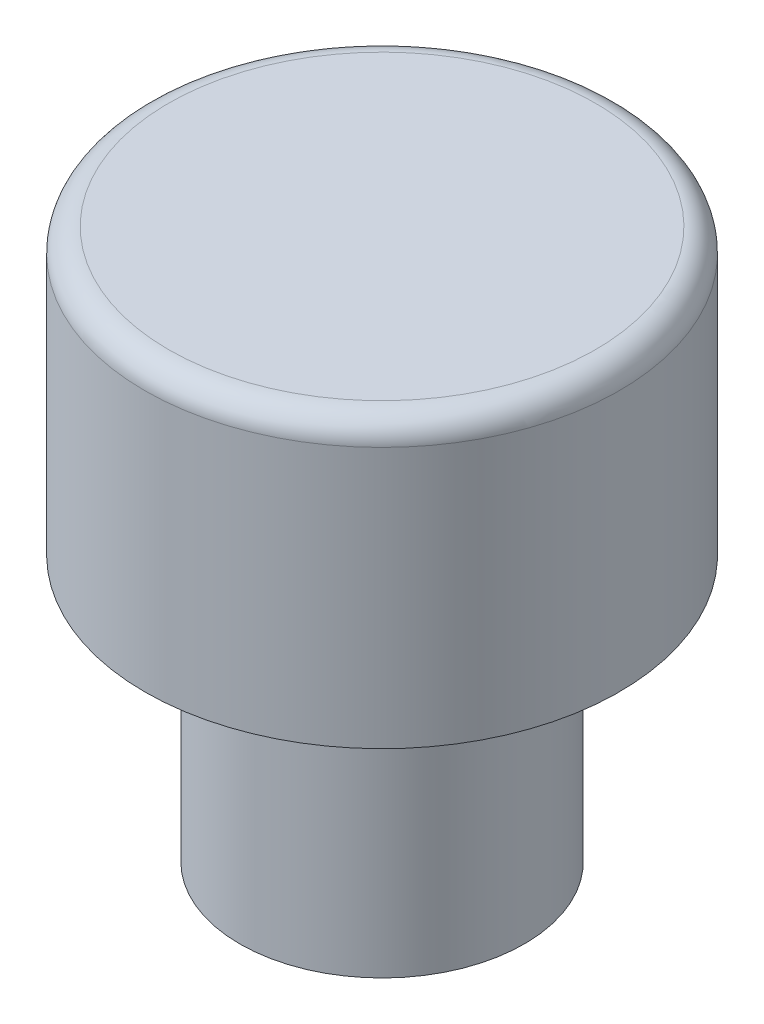
SolidWorks part; units mm, degrees
ref_plane "Front Plane" through (0, 0, 0) normal (0, 0, 1) x (1, 0, 0)
ref_plane "Top Plane" through (0, 0, 0) normal (0, 1, 0) x (1, 0, 0)
ref_plane "Right Plane" through (0, 0, 0) normal (1, 0, 0) x (0, 0, -1)
sketch "Sketch1" plane through (0, 0, 0) normal (0, 1, 0) x (1, 0, 0)
  line L0 (0, -2.05) -> (0, 2.05) construction
  line L1 (-2.05, 0) -> (2.05, 0) construction
  line L2 (-0.585, 0.885) -> (-0.585, 2.05)
  line L3 (-0.585, -2.05) -> (0.585, -2.05)
  line L4 (-0.585, -2.05) -> (-0.585, -0.885)
  line L5 (-0.585, 2.05) -> (0.585, 2.05)
  line L6 (0.585, -2.05) -> (0.585, -0.885)
  line L7 (-0.585, -2.05) -> (0.585, 2.05) construction
  line L8 (-0.585, 2.05) -> (0.585, -2.05) construction
  line L9 (-2.05, -0.585) -> (-0.885, -0.585)
  line L10 (-2.05, -0.585) -> (-2.05, 0.585)
  line L11 (-2.05, 0.585) -> (-0.885, 0.585)
  line L12 (2.05, -0.585) -> (2.05, 0.585)
  line L13 (-2.05, -0.585) -> (2.05, 0.585) construction
  line L14 (-2.05, 0.585) -> (2.05, -0.585) construction
  line L15 (0.885, 0.585) -> (2.05, 0.585)
  line L16 (0.585, 0.885) -> (0.585, 2.05)
  line L17 (0.885, -0.585) -> (2.05, -0.585)
  circle A0 centre (0, 0) radius 3
  arc A1 (-0.585, -0.885) -> (-0.885, -0.585) centre (-0.885, -0.885) ccw
  arc A2 (0.585, -0.885) -> (0.885, -0.585) centre (0.885, -0.885) cw
  arc A3 (0.885, 0.585) -> (0.585, 0.885) centre (0.885, 0.885) cw
  arc A4 (-0.585, 0.885) -> (-0.885, 0.585) centre (-0.885, 0.885) cw
  point P5 (0, 0)
  point P8 (0, 0)
  point P20 (2.05, 0)
  point P21 (0, 2.05)
  point P30 (0, 0)
  dimension "D1" = 6
  dimension "D4" = 0.3
  dimension "D2" = 4.1
  dimension "D3" = 1.17
extrude "stem housing" add sketch "Sketch1" along normal blind 5.6
sketch "Sketch2" plane through (0, 5.6, 0) normal (0, 1, 0) x (1, 0, 0)
  circle A0 centre (0, 0) radius 5
  dimension "D1" = 10
extrude "button head" add sketch "Sketch2" along normal blind 6
fillet "Fillet1" radius 0.5 1 edges at (0, 11.6, 5)
